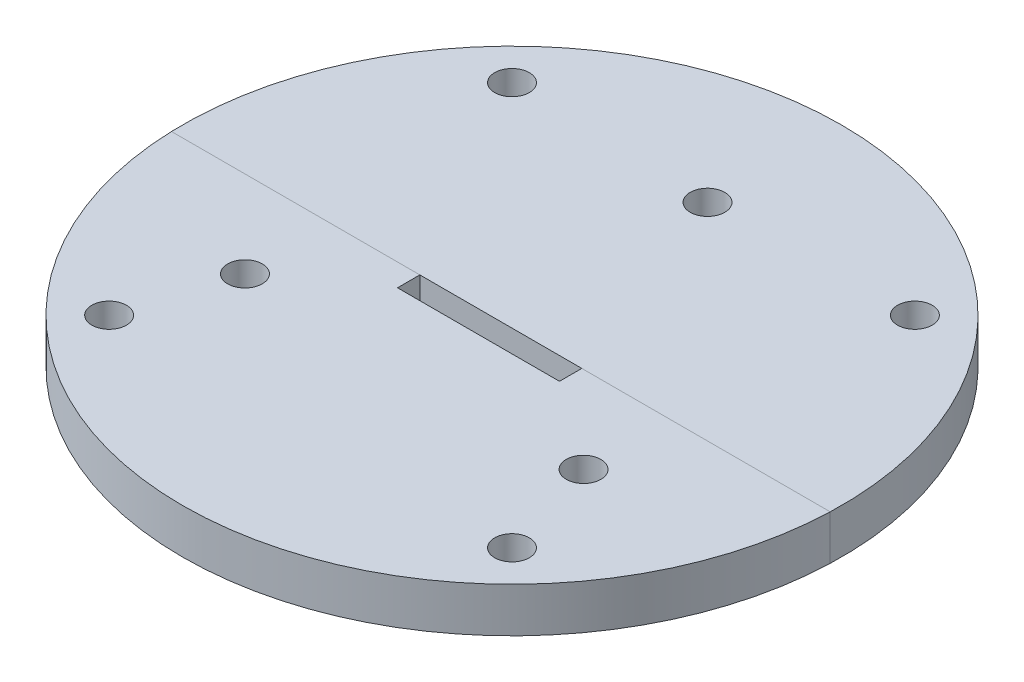
SolidWorks part; units mm, degrees
ref_plane "Front Plane" through (0, 0, 0) normal (0, 0, 1) x (1, 0, 0)
ref_plane "Top Plane" through (0, 0, 0) normal (0, 1, 0) x (1, 0, 0)
ref_plane "Right Plane" through (0, 0, 0) normal (1, 0, 0) x (0, 0, -1)
sketch "Sketch1" plane through (0, 0, 0) normal (0, 1, 0) x (1, 0, 0)
  circle A0 centre (0, 0) radius 29.5
  dimension "D1" = 59
extrude "Boss-Extrude1" add sketch "Sketch1" along normal blind 4
sketch "Sketch2" plane through (0, 4, 0) normal (0, 1, 0) x (1, 0, 0)
  line L0 (0, 0) -> (0, 13.0142) construction
  circle A0 centre (-18.0312, 18.0312) radius 1.55
  dimension "D1" = 3.1
  dimension "D2" = 25.5
  dimension "D3" = 45
extrude "Cut-Extrude1" cut sketch "Sketch2" against normal through all
pattern_circular "CirPattern1" count 4 over 360 about axis through (0, 0, 0) along (0, 1, 0) of "Cut-Extrude1"
sketch "Sketch3" plane through (0, 4, 0) normal (0, 1, 0) x (1, 0, 0)
  line L0 (-29.5, 0) -> (29.5, 0) construction
  line L6 (-7.25, -1) -> (7.25, -1)
  line L7 (-7.25, -1) -> (-7.25, -3)
  line L8 (-7.25, -3) -> (7.25, -3)
  line L9 (7.25, -1) -> (7.25, -3)
  circle A0 centre (0, 0) radius 29.5 construction
  dimension "D1" = 2
  dimension "D2" = 7.25
  dimension "D3" = 7.25
  dimension "D4" = 3
extrude "Cut-Extrude2" cut sketch "Sketch3" against normal through all
sketch "Sketch9" plane through (0, 4, 0) normal (0, 1, 0) x (1, 0, 0)
  circle A0 centre (0, 0) radius 21.5
  circle A1 centre (0, 17.5) radius 1.55
  dimension "D1" = 3.1
  dimension "D2" = 17.5
extrude "Cut-Extrude3" cut sketch "Sketch9" against normal through all contours A1
pattern_circular "CirPattern4" count 3 over 360 about axis through (0, 0, 0) along (0, 1, 0) of "Cut-Extrude3"
sketch "Sketch8" plane through (0, 0, 0) normal (0, 1, 0) x (1, 0, 0)
  line L0 (-30.6617, -1) -> (30.6617, -1)
  dimension "D1" = 1
split "Split1" trim tools "Sketch8" bodies to split 110 resulting bodies 111 112
